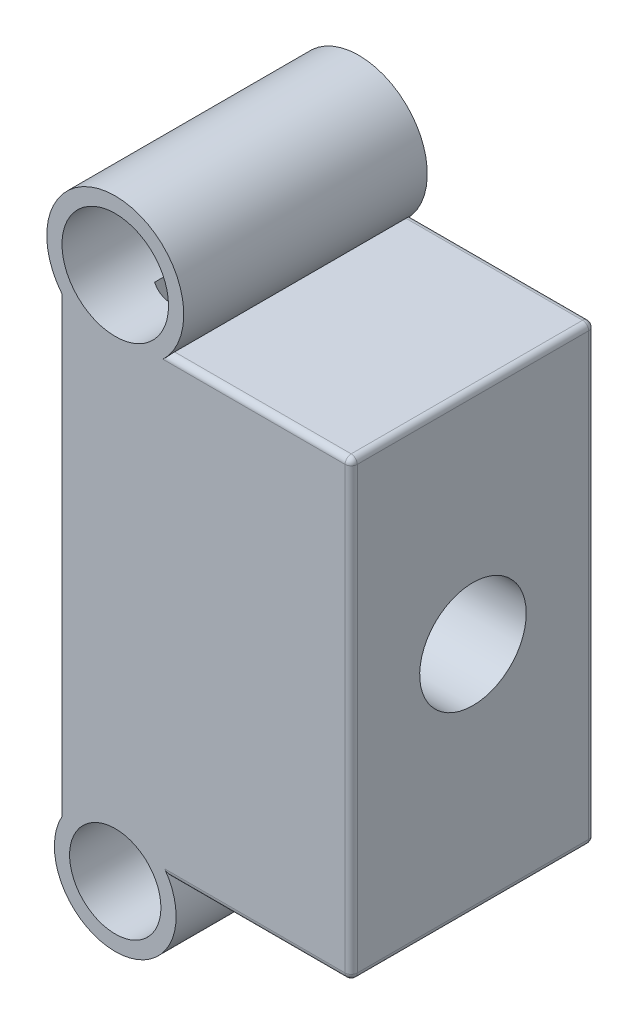
SolidWorks part; units mm, degrees
ref_plane "Front Plane" through (0, 0, 0) normal (0, 0, 1) x (1, 0, 0)
ref_plane "Top Plane" through (0, 0, 0) normal (0, 1, 0) x (1, 0, 0)
ref_plane "Right Plane" through (0, 0, 0) normal (1, 0, 0) x (0, 0, -1)
sketch "Sketch1" plane through (0, 0, 0) normal (0, 0, 1) x (1, 0, 0)
  line L0 (61.7733, 63.75) -> (-110.0664, 63.75) construction
  line L1 (74.066, -66.25) -> (-84.8712, -66.25) construction
  line L2 (0, 86.25) -> (0, -86.25) construction
  line L6 (-17.5, 72.1079) -> (-17.5, 63.75)
  line L7 (-17.5, -66.25) -> (-17.5, -76.5675)
  line L15 (-17.5, 63.75) -> (-17.5, -66.25)
  line L17 (17.5, 72.1079) -> (77.5, 72.1079)
  line L19 (17.5, -76.5675) -> (77.5, -76.5675)
  line L20 (77.5, 72.1079) -> (77.5, -76.5675)
  circle A7 centre (0, 86.25) radius 17.5
  arc A8 (17.5, 72.1079) -> (-17.5, 72.1079) centre (0, 86.25) ccw
  circle A9 centre (0, -86.25) radius 15
  arc A10 (-17.5, -76.5675) -> (17.5, -76.5675) centre (0, -86.25) ccw
  dimension "D6" = 60
  dimension "D3" = 35
  dimension "D5" = 130
  dimension "D1" = 40
  dimension "D2" = 30
  dimension "D4" = 45
extrude "Boss-Extrude1" add sketch "Sketch1" along normal blind 80
ref_plane "Plane1" through (0, 0, 40) normal (0, 0, 1) x (1, 0, 0)
sketch "Sketch9" plane through (0, 0, 40) normal (0, 0, 1) x (1, 0, 0)
  line L0 (-48.2115, 47.7702) -> (170.952, 47.7702) construction
  line L1 (-17.5, -2.2298) -> (199.0323, -2.2298) construction
  line L2 (-17.5, 72.1079) -> (-17.5, -76.5675) construction
  line L3 (0, 86.25) -> (0, -123.4539) construction
  line L4 (-7.3536, 47.7702) -> (-7.3536, 17.7702)
  line L5 (-7.3536, 17.7702) -> (6.6464, 17.7702)
  line L11 (-7.3536, 47.7702) -> (62.2831, 47.7702)
  line L12 (6.6464, 17.7702) -> (6.6464, 45.2702)
  line L13 (6.6464, 45.2702) -> (12.2831, 45.2702)
  line L14 (12.2831, 45.2702) -> (12.2831, 30.2702)
  line L15 (12.2831, 30.2702) -> (62.2831, 30.2702)
  line L16 (62.2831, 30.2702) -> (62.2831, 47.7702)
  dimension "D1" = 50
  dimension "D2" = 30
  dimension "D3" = 2.5
  dimension "D4" = 15
  dimension "D5" = 50
revolve "Cut-Revolve1" cut sketch "Sketch9" angle 360 about L0
sketch "Sketch38" plane through (0, 0, 40) normal (0, 0, 1) x (1, 0, 0)
  line L0 (0, 86.25) -> (0, -86.25) construction
  line L1 (-47.578, 0) -> (116.2513, 0) construction
  line L2 (17, 0) -> (17, 12.5)
  line L3 (17, -45.2407) -> (17, 57.6515) construction
  line L4 (17, 12.5) -> (22.4752, 12.5)
  line L5 (22.4752, 12.5) -> (22.4752, 17.5)
  line L6 (22.4752, 17.5) -> (102.0526, 17.5)
  line L7 (102.0526, 17.5) -> (102.0526, 0)
  line L8 (102.0526, 0) -> (17, 0)
  point P7 (17, 0)
  dimension "D1" = 17
  dimension "D2" = 12.5
  dimension "D3" = 5
revolve "Cut-Revolve3" cut sketch "Sketch38" angle 360 about L8
sketch "Sketch60" plane through (0, 0, 40) normal (0, 0, 1) x (1, 0, 0)
  line L0 (57.7512, 47.8448) -> (68.2111, 47.8448)
  line L1 (68.2111, 47.8448) -> (68.2111, 23.4949)
  line L2 (68.2111, 23.4949) -> (19.1596, 23.4949)
  line L3 (19.1596, 23.4949) -> (19.1596, 12.0712)
sweep "Cut-Sweep3" cut path "Sketch60" circular profile diameter 4 parameters "D3"=4
fillet "Fillet2" radius 2 8 edges at (47.5, -76.5675, 0) (47.5, 72.1079, 0) (77.5, -2.2298, 0) (77.5, -76.5675, 40) (47.5, -76.5675, 80) (77.5, -2.2298, 80) (77.5, 72.1079, 40) (47.5, 72.1079, 80)
